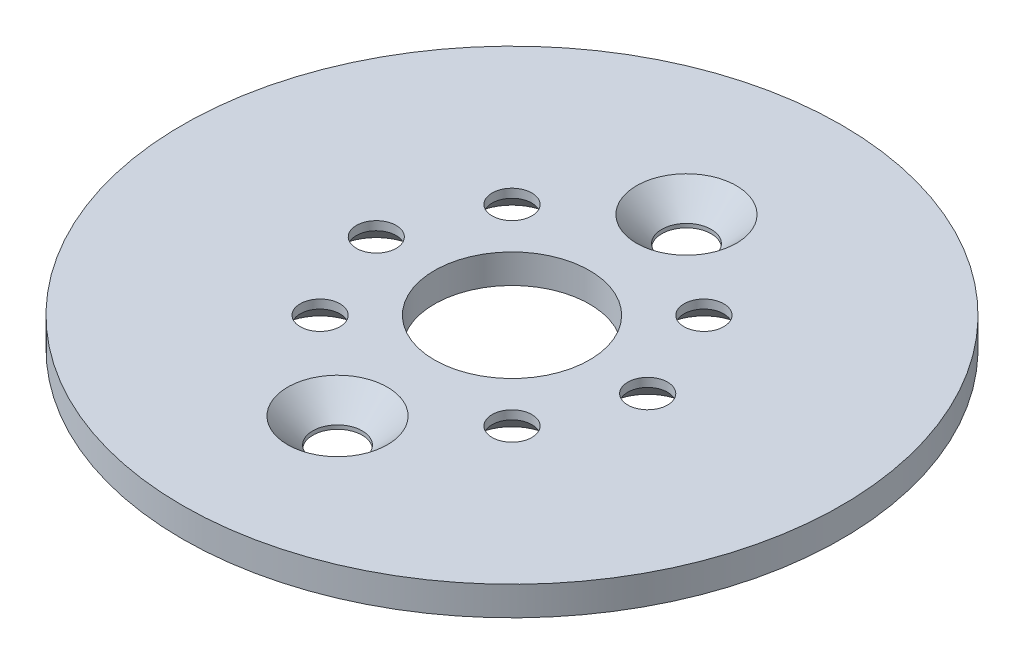
SolidWorks part; units mm, degrees
material "Thornel Mat VMA"
ref_plane "前视基准面" through (0, 0, 0) normal (0, 0, 1) x (1, 0, 0)
ref_plane "上视基准面" through (0, 0, 0) normal (0, 1, 0) x (1, 0, 0)
ref_plane "右视基准面" through (0, 0, 0) normal (1, 0, 0) x (0, 0, -1)
sketch "草图1" plane through (0, 0, 0) normal (0, 1, 0) x (1, 0, 0)
  circle A0 centre (0, 0) radius 34
  circle A1 centre (0, 0) radius 8
  circle A2 centre (0, 0) radius 14 construction
  circle A3 centre (0, 14) radius 2.05
  circle A4 centre (9.8995, 9.8995) radius 2.05
  circle A5 centre (14, 0) radius 2.05
  circle A6 centre (9.8995, -9.8995) radius 2.05
  circle A7 centre (0, -14) radius 2.05
  circle A8 centre (-9.8995, -9.8995) radius 2.05
  circle A9 centre (-14, 0) radius 2.05
  circle A10 centre (-9.8995, 9.8995) radius 2.05
  point P24 (0, 0)
  dimension "D1" = 68
  dimension "D2" = 16
  dimension "D3" = 28
  dimension "D4" = 4.1
  dimension "D5" = 8
extrude "凸台-拉伸1" add sketch "草图1" along normal blind 3 contours A0 | A10 | A9 | A8 | A1 | A4 | A5 | A6
ref_plane "基准面1" through (0, 0, 0) normal (0, -1, 0) x (-1, 0, 0)
ref_plane "基准面2" through (0, 0, 0) normal (0, -1, 0) x (-1, 0, 0)
sketch "草图2" plane through (0, 0, 0) normal (0, -1, 0) x (-1, 0, 0)
  line L0 (0, 34) -> (0, -34) construction
  circle A0 centre (0, 0) radius 34 construction
  circle A1 centre (0, 18) radius 2.55
  circle A2 centre (0, -18) radius 2.55
  dimension "D2" = 5.1
  dimension "D4" = 5.1
  dimension "D1" = 18
  dimension "D3" = 18
extrude "切除-拉伸1" cut sketch "草图2" against normal blind 10
chamfer "倒角1" distance 2.1 angle 45 6 edges at (-9.8995, 0, 11.9495) (-14, 0, 2.05) (-9.8995, 0, -7.8495) (9.8995, 0, -7.8495) (14, 0, 2.05) (9.8995, 0, 11.9495)
chamfer "倒角2" distance 2.6 angle 45 2 edges at (0, 3, 20.55) (0, 3, -15.45)
